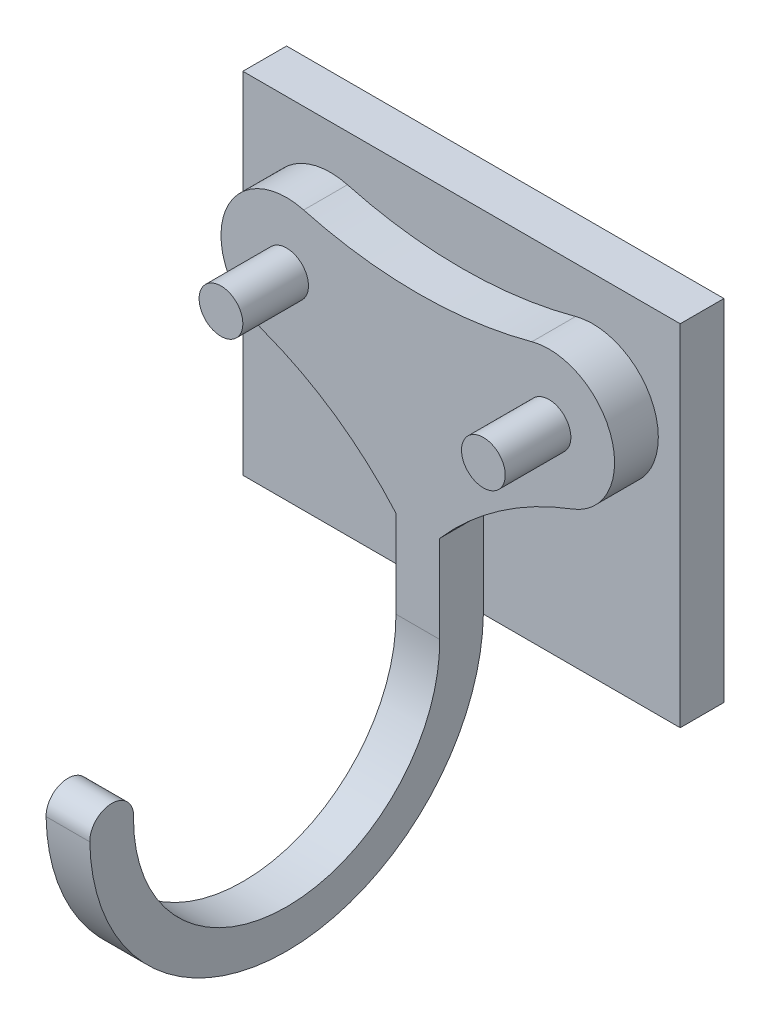
SolidWorks part; units mm, degrees
ref_plane "Alzado" through (0, 0, 0) normal (0, 0, 1) x (1, 0, 0)
ref_plane "Planta" through (0, 0, 0) normal (0, 1, 0) x (1, 0, 0)
ref_plane "Vista lateral" through (0, 0, 0) normal (1, 0, 0) x (0, 0, -1)
sketch "Croquis2" plane through (0, 0, 0) normal (0, 0, 1) x (1, 0, 0)
  line L1 (-10, -8) -> (10, -8)
  line L2 (-10, -8) -> (-10, 8)
  line L3 (-10, 8) -> (10, 8)
  line L4 (10, -8) -> (10, 8)
  line L5 (-10, -8) -> (10, 8) construction
  line L6 (-10, 8) -> (10, -8) construction
  point P0 (0, 0)
  dimension "D1" = 20
  dimension "D2" = 16
extrude "Saliente-Extruir1" add sketch "Croquis2" along normal blind 2 contours L3 L4 L1 L2
sketch "Croquis3" plane through (0, 0, 2) normal (0, 0, 1) x (1, 0, 0)
  line L0 (-10, 8) -> (10, 8) construction
  line L1 (0, 5.2036) -> (0, 8) construction
  line L2 (1, -8) -> (1, -4)
  line L3 (-10, -8) -> (10, -8) construction
  line L4 (-1, -8) -> (-1, -4)
  line L5 (-1, -8) -> (1, -8)
  arc A0 (-5.2174, 5.8961) -> (-7.0507, 0.19) centre (-6, 3) ccw
  arc A1 (5.2174, 5.8961) -> (7.0507, 0.19) centre (6, 3) cw
  arc A2 (-5.2174, 5.8961) -> (5.2174, 5.8961) centre (0, 25.2036) ccw
  arc A3 (-7.0507, 0.19) -> (-1, -4) centre (-12.304, -13.86) cw
  arc A4 (1, -4) -> (7.0507, 0.19) centre (12.304, -13.86) cw
  dimension "D1" = 6
  dimension "D4" = 20
  dimension "D6" = 15
  dimension "D8" = 15
  dimension "D2" = 6
  dimension "D3" = 5
  dimension "D7" = 4
extrude "Saliente-Extruir2" add sketch "Croquis3" along normal blind 2
sketch "Croquis4" plane through (0, 0, 4) normal (0, 0, 1) x (1, 0, 0)
  line L0 (0, 0) -> (0, 2.2805) construction
  circle A0 centre (-6, 3) radius 1
  circle A1 centre (6, 3) radius 1
  dimension "D1" = 2
extrude "Saliente-Extruir3" add sketch "Croquis4" along normal blind 3
sketch "Croquis5" plane through (0, 0, 0) normal (1, 0, 0) x (0, 0, -1)
  line L0 (-4, -8) -> (-2.0012, -8)
  arc A0 (-19.9984, -8.0187) -> (-2.0012, -8) centre (-11, -7.851) ccw
  arc A2 (-17.9993, -8.1096) -> (-19.9984, -8.0187) centre (-18.996, -8) ccw
  arc A3 (-4, -8) -> (-17.9993, -8.1096) centre (-10.9994, -8.0952) cw
  dimension "D2" = 18
  dimension "D3" = 7
  dimension "D1" = 9
extrude "Saliente-Extruir4" add sketch "Croquis5" along normal blind 1 and the other way blind 1 contours A3 A2 A0 L0
